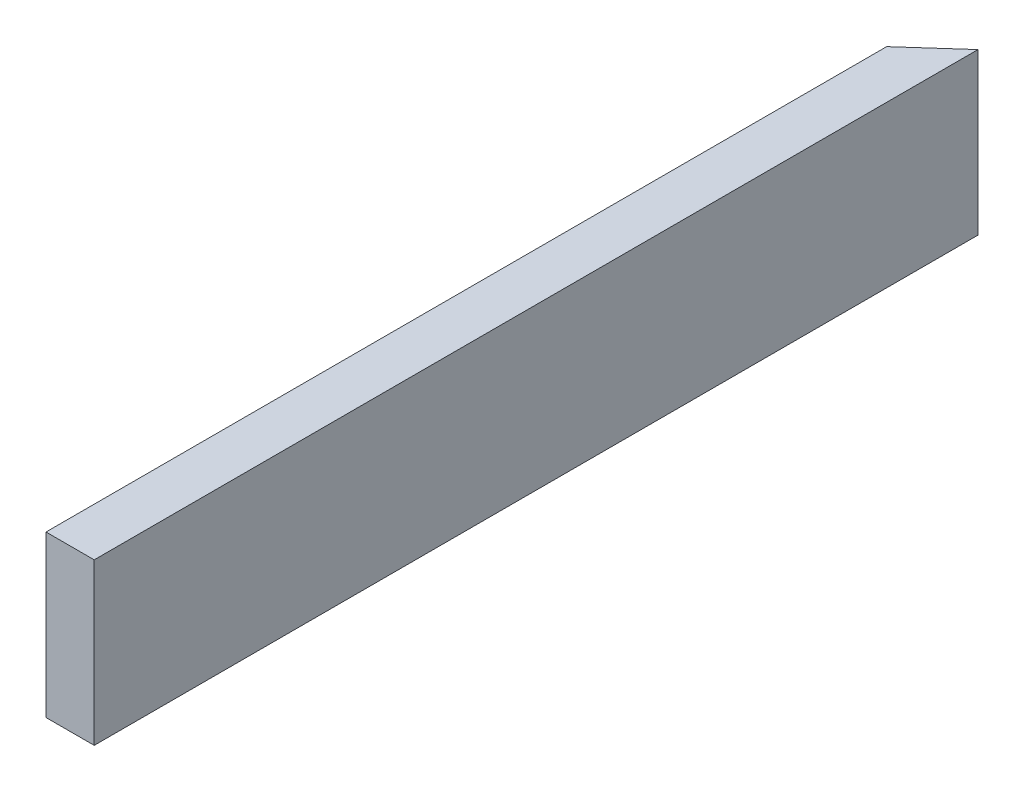
SolidWorks part; units mm, degrees
ref_plane "Front Plane" through (0, 0, 0) normal (0, 0, 1) x (1, 0, 0)
ref_plane "Top Plane" through (0, 0, 0) normal (0, 1, 0) x (1, 0, 0)
ref_plane "Right Plane" through (0, 0, 0) normal (1, 0, 0) x (0, 0, -1)
sketch "Sketch1" plane through (0, 0, 0) normal (0, 0, 1) x (1, 0, 0)
  line L1 (-3.9032, 12.8387) -> (-0.9032, 12.8387)
  line L2 (-3.9032, 12.8387) -> (-3.9032, 2.8387)
  line L3 (-3.9032, 2.8387) -> (-0.9032, 2.8387)
  line L4 (-0.9032, 12.8387) -> (-0.9032, 2.8387)
  dimension "D1" = 3
  dimension "D2" = 10
extrude "Boss-Extrude1" add sketch "Sketch1" along normal blind 55
ref_plane "Plane1" through (0, 12.8387, 0) normal (0, 1, 0) x (1, 0, 0)
sketch "Sketch3" plane through (0, 12.8387, 0) normal (0, 1, 0) x (1, 0, 0)
  line L0 (-0.9032, 0) -> (-3.9032, -2.6823)
  line L1 (-3.9032, -55) -> (-3.9032, 0) construction
  line L2 (-3.9032, -2.6823) -> (-3.9032, 0)
  line L3 (-3.9032, 0) -> (-0.9032, 0)
  dimension "D1" = 41.8
extrude "Cut-Extrude1" cut sketch "Sketch3" against normal blind 52
